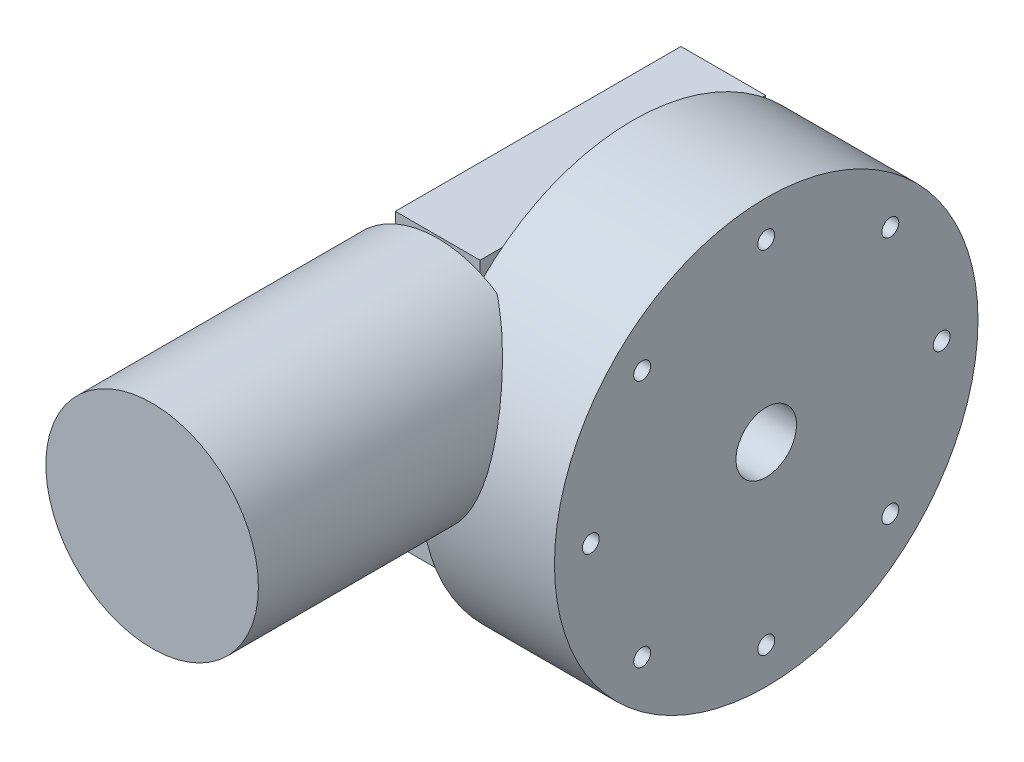
SolidWorks part; units mm, degrees
material "Malleable Cast Iron"
ref_plane "Front Plane" through (0, 0, 0) normal (0, 0, 1) x (1, 0, 0)
ref_plane "Top Plane" through (0, 0, 0) normal (0, 1, 0) x (1, 0, 0)
ref_plane "Right Plane" through (0, 0, 0) normal (1, 0, 0) x (0, 0, -1)
sketch "Sketch1" plane through (0, 0, 0) normal (1, 0, 0) x (0, 0, -1)
  circle A0 centre (0, 0) radius 175
  dimension "D1" = 350
extrude "Boss-Extrude1" add sketch "Sketch1" along normal blind 110.5
sketch "Sketch2" plane through (0, 0, 0) normal (-1, 0, 0) x (0, 0, 1)
  circle A0 centre (0, 0) radius 145 construction
  circle A1 centre (0, 145) radius 7
  dimension "D1" = 290
  dimension "D2" = 14
extrude "Cut-Extrude1" cut sketch "Sketch2" against normal through all
pattern_circular "CirPattern1" count 8 over 360 about axis through (0, 0, 0) along (1, 0, 0) of "Cut-Extrude1"
sketch "Sketch4" plane through (0, 0, 0) normal (1, 0, 0) x (0, 0, -1)
  line L1 (110, -100.5235) -> (-126, -100.5235)
  line L2 (110, -100.5235) -> (110, 138)
  line L3 (110, 138) -> (-126, 138)
  line L4 (-126, -100.5235) -> (-126, 138)
  dimension "D1" = 110
  dimension "D2" = 126
  dimension "D3" = 138
extrude "Boss-Extrude2" add sketch "Sketch4" against normal blind 70 separate body
sketch "Sketch5" plane through (0, 0, 126) normal (0, 0, 1) x (1, 0, 0)
  line L0 (-70, 138) -> (0, 138) construction
  circle A0 centre (-35, 48.3972) radius 87.8281
  point P5 (-35, 138)
  dimension "D1" = 175.6561
extrude "Boss-Extrude3" add sketch "Sketch5" along normal blind 236
sketch "Sketch6" plane through (110.5, 0, 0) normal (1, 0, 0) x (0, 0, -1)
  circle A0 centre (0, 0) radius 25
  dimension "D1" = 50
extrude "Cut-Extrude2" cut sketch "Sketch6" against normal through all
